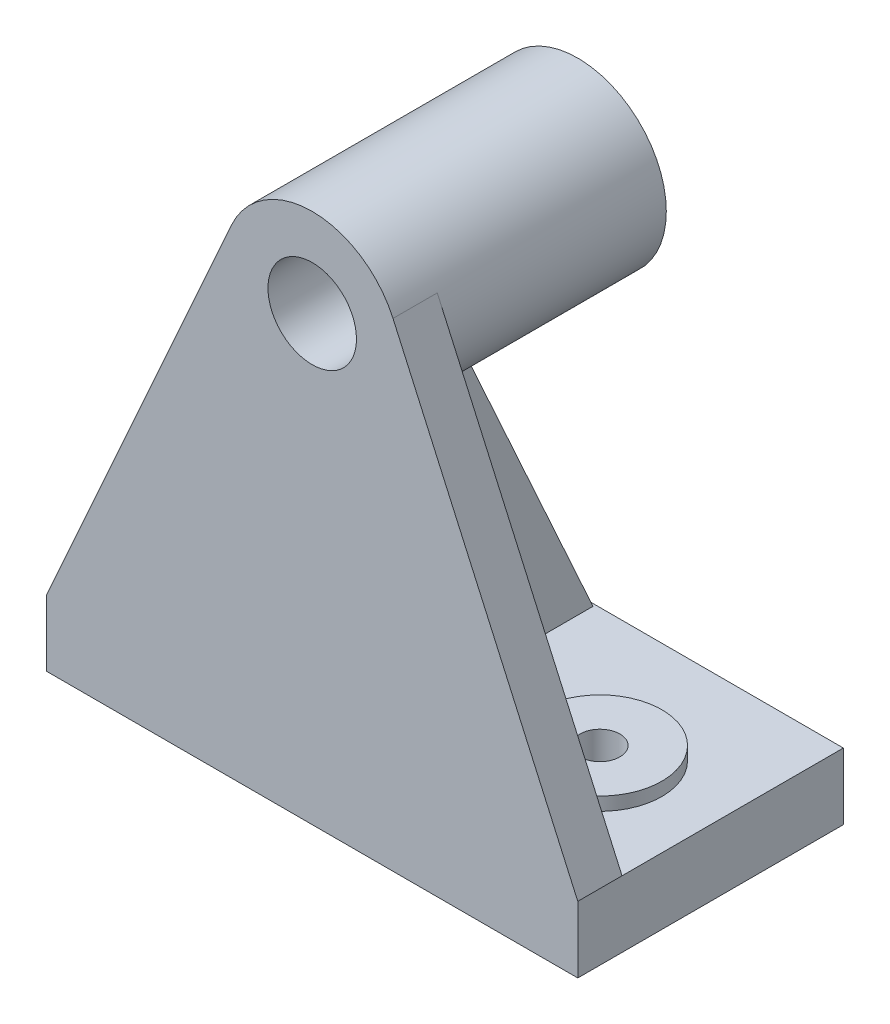
SolidWorks part; units mm, degrees
ref_plane "Front Plane" through (0, 0, 0) normal (0, 0, 1) x (1, 0, 0)
ref_plane "Top Plane" through (0, 0, 0) normal (0, 1, 0) x (1, 0, 0)
ref_plane "Right Plane" through (0, 0, 0) normal (1, 0, 0) x (0, 0, -1)
sketch "Sketch1" plane through (0, 0, 0) normal (0, 1, 0) x (1, 0, 0)
  line L1 (-60, 30) -> (60, 30)
  line L2 (-60, 30) -> (-60, -30)
  line L3 (-60, -30) -> (60, -30)
  line L4 (60, 30) -> (60, -30)
  line L5 (-60, 30) -> (60, -30) construction
  line L6 (-60, -30) -> (60, 30) construction
  circle A0 centre (-35, 0) radius 4.5
  circle A1 centre (35, 0) radius 4.5
  point P0 (0, 0)
  dimension "D3" = 25
  dimension "D1" = 120
  dimension "D2" = 60
  dimension "D4" = 70
extrude "Boss-Extrude1" add sketch "Sketch1" against normal blind 15
sketch "Sketch2" plane through (0, 0, 30) normal (0, 0, 1) x (1, 0, 0)
  line L0 (0, -15) -> (0, 85) construction
  line L1 (-60, -15) -> (60, -15) construction
  circle A0 centre (0, 85) radius 10
  circle A1 centre (0, 85) radius 20
  dimension "D1" = 100
extrude "Boss-Extrude2" add sketch "Sketch2" against normal blind 60 separate body
sketch "Sketch3" plane through (0, 0, 30) normal (0, 0, 1) x (1, 0, 0)
  line L0 (-60, 0) -> (-18.2517, 93.1777)
  line L1 (60, 0) -> (18.2517, 93.1777)
  line L2 (-60, 0) -> (60, 0)
  circle A0 centre (0, 85) radius 20 construction
  circle A2 centre (0, 85) radius 20
  arc A3 (-18.2517, 93.1777) -> (18.2517, 93.1777) centre (0, 85) ccw
  dimension "D1" = 0
extrude "Boss-Extrude3" add sketch "Sketch3" against normal blind 10
sketch "Sketch11" plane through (0, 0, 0) normal (0, 1, 0) x (1, 0, 0)
  circle A0 centre (-35, 0) radius 14
  circle A1 centre (35, 0) radius 14
  circle A2 centre (35, 0) radius 4.5
  circle A3 centre (-35, 0) radius 4.5
extrude "Boss-Extrude4" add sketch "Sketch11" along normal blind 3
sketch "Sketch13" plane through (0, 0, 0) normal (1, 0, 0) x (0, 0, -1)
  line L0 (29.4274, 0) -> (0, 65)
  line L1 (0, 65) -> (30, 65) construction
rib "Rib1" sketch "Sketch13" sketch "Sketch13" thickness 8 extrusion direction parallel to sketch draft on no parameters "D1"=8
fillet "Fillet1" radius 2 1 edges at (0, 65, 0)
